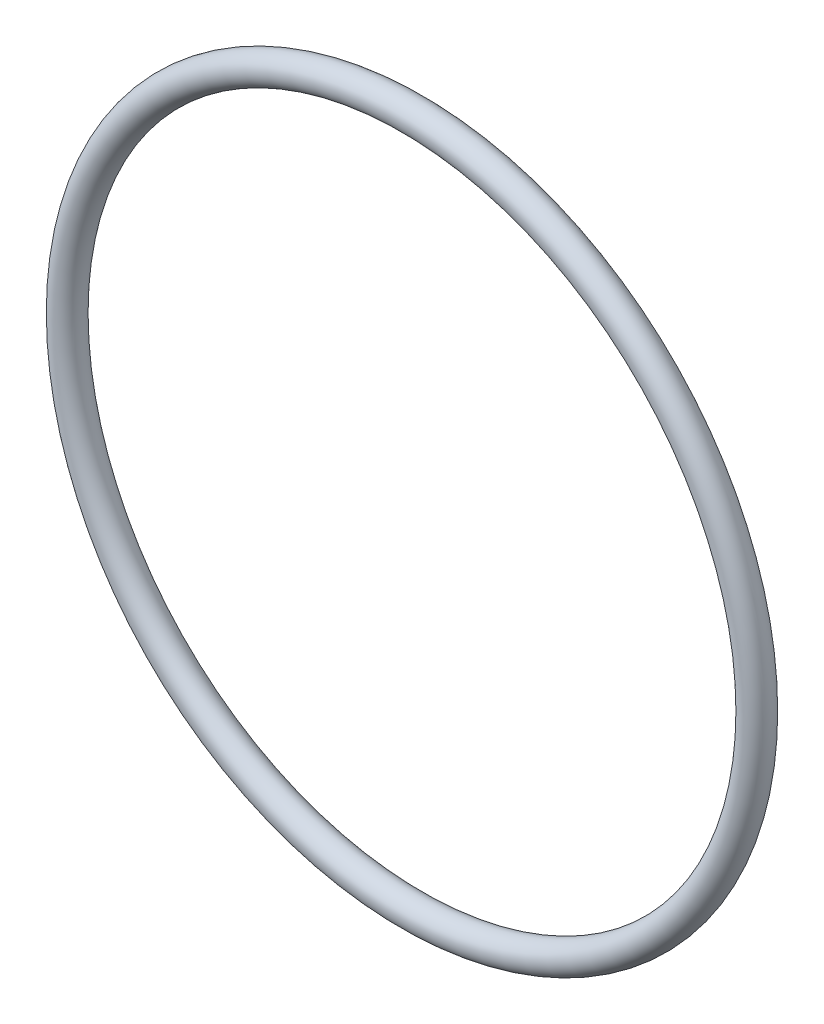
SolidWorks part; units mm, degrees
ref_plane "前视基准面" through (0, 0, 0) normal (0, 0, 1) x (1, 0, 0)
ref_plane "上视基准面" through (0, 0, 0) normal (0, 1, 0) x (1, 0, 0)
ref_plane "右视基准面" through (0, 0, 0) normal (1, 0, 0) x (0, 0, -1)
other "Configuration Table"
sketch "Sk_oring67" plane through (0, 0, 0) normal (0, 1, 0) x (1, 0, 0)
  line L0 (0, 0) -> (0, -2) construction
  circle A0 centre (35, 0) radius 1.5
revolve "Rev_oring67" add sketch "Sk_oring67" angle 360 about L0
